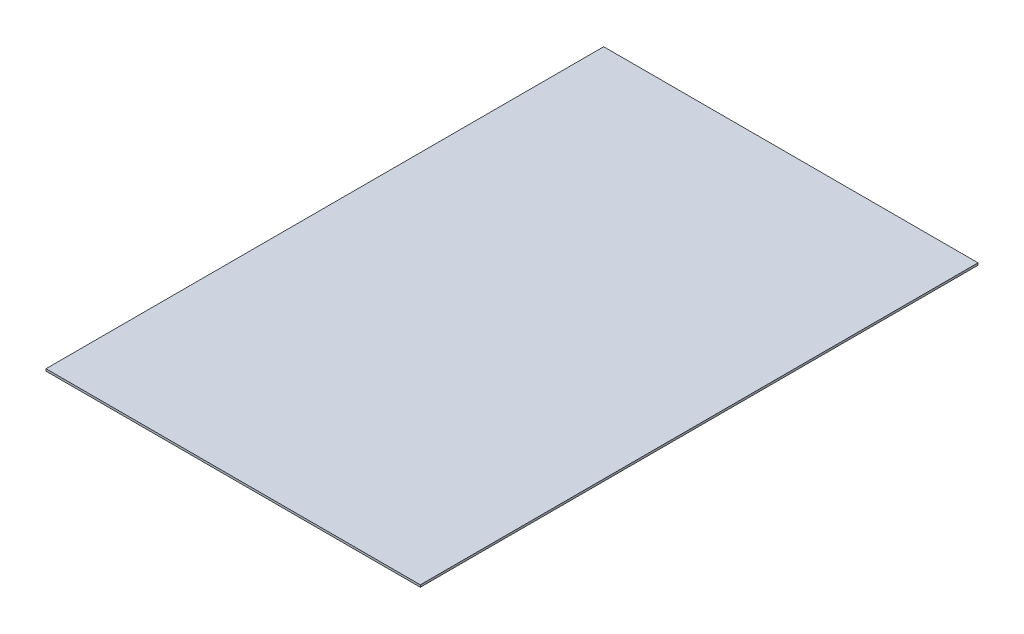
SolidWorks part; units mm, degrees
ref_plane "Alzado" through (0, 0, 0) normal (0, 0, 1) x (1, 0, 0)
ref_plane "Planta" through (0, 0, 0) normal (0, 1, 0) x (1, 0, 0)
ref_plane "Vista lateral" through (0, 0, 0) normal (1, 0, 0) x (0, 0, -1)
sketch "Croquis1" plane through (0, 0, 0) normal (0, 1, 0) x (1, 0, 0)
  line L1 (-174.5, 260) -> (174.5, 260)
  line L2 (-174.5, 260) -> (-174.5, -260)
  line L3 (-174.5, -260) -> (174.5, -260)
  line L4 (174.5, 260) -> (174.5, -260)
  line L5 (-174.5, 260) -> (174.5, -260) construction
  line L6 (-174.5, -260) -> (174.5, 260) construction
  point P0 (0, 0)
  dimension "D1" = 349
  dimension "D2" = 520
extrude "Saliente-Extruir1" add sketch "Croquis1" along normal blind 2
